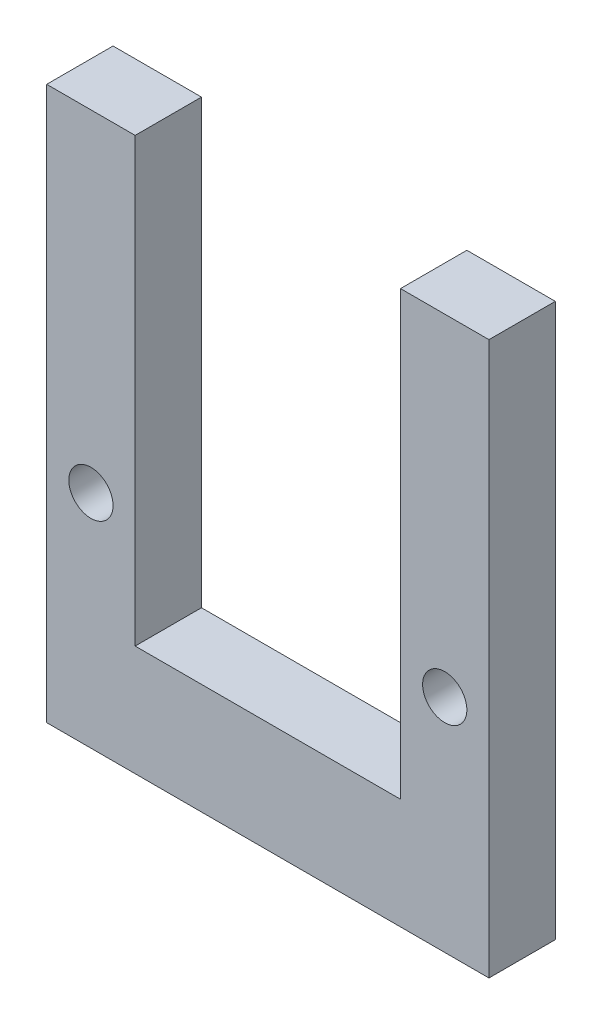
SolidWorks part; units mm, degrees
ref_plane "Front Plane" through (0, 0, 0) normal (0, 0, 1) x (1, 0, 0)
ref_plane "Top Plane" through (0, 0, 0) normal (0, 1, 0) x (1, 0, 0)
ref_plane "Right Plane" through (0, 0, 0) normal (1, 0, 0) x (0, 0, -1)
sketch "Sketch3" plane through (0, 0, 0) normal (0, 0, 1) x (1, 0, 0)
  line L0 (-6, -7.5) -> (-6, 12.5)
  line L1 (-10, 12.5) -> (-6, 12.5)
  line L2 (-10, 12.5) -> (-10, -12.5)
  line L3 (-10, -12.5) -> (10, -12.5)
  line L4 (10, 12.5) -> (10, -12.5)
  line L5 (-10, 12.5) -> (10, -12.5) construction
  line L6 (-10, -12.5) -> (10, 12.5) construction
  line L7 (6, -7.5) -> (6, 12.5)
  line L8 (0, 20.5822) -> (0, -15.3284) construction
  line L9 (-6, -7.5) -> (6, -7.5)
  line L14 (6, 12.5) -> (10, 12.5)
  circle A0 centre (-8, -2.5) radius 1
  circle A1 centre (8, -2.5) radius 1
  point P0 (0, 0)
  point P6 (0, 0)
  dimension "D6" = 2
  dimension "D1" = 25
  dimension "D2" = 20
  dimension "D3" = 5
  dimension "D4" = 4
  dimension "D5" = 4
  dimension "D7" = 5
  dimension "D8" = 2
extrude "Boss-Extrude1" add sketch "Sketch3" along normal mid plane 3
